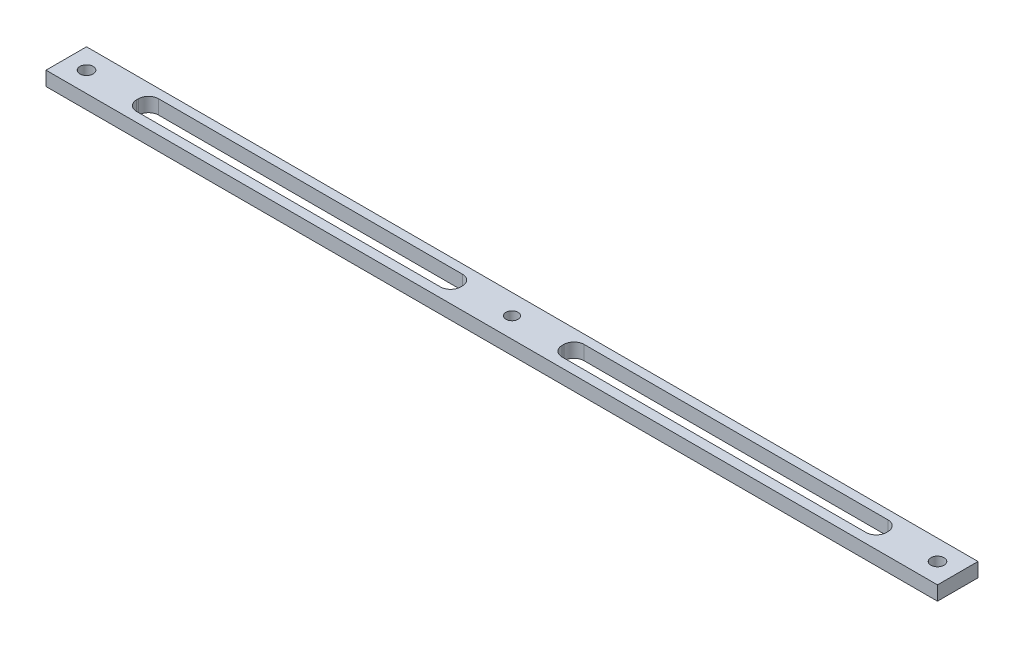
SolidWorks part; units mm, degrees
ref_plane "Płaszczyzna przednia" through (0, 0, 0) normal (0, 0, 1) x (1, 0, 0)
ref_plane "Płaszczyzna górna" through (0, 0, 0) normal (0, 1, 0) x (1, 0, 0)
ref_plane "Płaszczyzna prawa" through (0, 0, 0) normal (1, 0, 0) x (0, 0, -1)
sketch "Szkic1" plane through (0, 0, 0) normal (0, 1, 0) x (1, 0, 0)
  line L0 (220, 0) -> (220, 10)
  line L1 (0, 0) -> (440, 0)
  line L2 (0, 0) -> (0, 20)
  line L3 (0, 20) -> (440, 20)
  line L4 (440, 0) -> (440, 20)
  line L5 (0, 10) -> (10, 10)
  line L6 (440, 10) -> (430, 10)
  line L8 (40, 15.5746) -> (190, 15.5746)
  line L9 (35, 10.5746) -> (35, 9.6967)
  line L10 (40, 4.6967) -> (190, 4.6967)
  line L11 (195, 10.5746) -> (195, 9.6967)
  line L12 (250, 15.5746) -> (400, 15.5746)
  line L13 (245, 10.5746) -> (245, 9.7528)
  line L14 (250, 4.7528) -> (400, 4.7528)
  line L15 (405, 10.5746) -> (405, 9.7528)
  circle A0 centre (220, 10) radius 3
  circle A1 centre (10, 10) radius 3.25
  circle A2 centre (430, 10) radius 3.25
  arc A3 (400, 4.7528) -> (405, 9.7528) centre (400, 9.7528) ccw
  arc A4 (405, 10.5746) -> (400, 15.5746) centre (400, 10.5746) ccw
  arc A5 (250, 4.7528) -> (245, 9.7528) centre (250, 9.7528) cw
  arc A6 (250, 15.5746) -> (245, 10.5746) centre (250, 10.5746) ccw
  arc A7 (35, 9.6967) -> (40, 4.6967) centre (40, 9.6967) ccw
  arc A8 (190, 4.6967) -> (195, 9.6967) centre (190, 9.6967) ccw
  arc A9 (195, 10.5746) -> (190, 15.5746) centre (190, 10.5746) ccw
  arc A10 (40, 15.5746) -> (35, 10.5746) centre (40, 10.5746) ccw
  dimension "D1" = 5
  dimension "D2" = 20
  dimension "D6" = 6.5
  dimension "D7" = 6
  dimension "D8" = 6.5
  dimension "D11" = 35
  dimension "D3" = 440
  dimension "D4" = 150
  dimension "D5" = 150
  dimension "D9" = 10
  dimension "D10" = 10
  dimension "D12" = 35
extrude "Dodanie-wyciągnięcie1" add sketch "Szkic1" along normal blind 7
